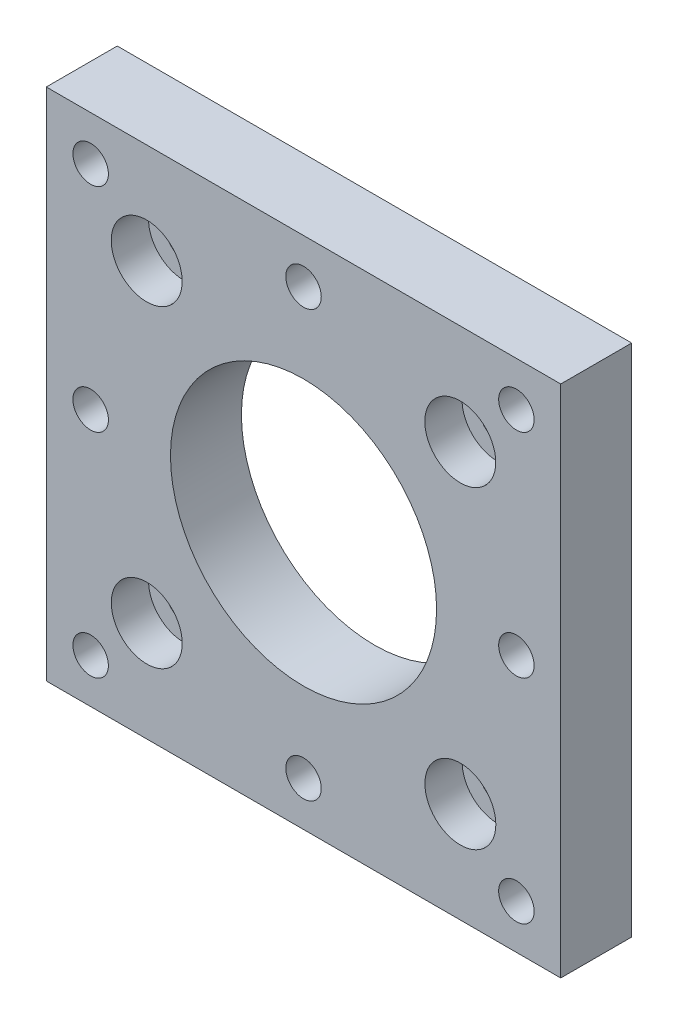
SolidWorks part; units mm, degrees
ref_plane "Front Plane" through (0, 0, 0) normal (0, 0, 1) x (1, 0, 0)
ref_plane "Top Plane" through (0, 0, 0) normal (0, 1, 0) x (1, 0, 0)
ref_plane "Right Plane" through (0, 0, 0) normal (1, 0, 0) x (0, 0, -1)
sketch "Sketch1" plane through (0, 0, 0) normal (0, 0, 1) x (1, 0, 0)
  line L0 (0, 0) -> (0, 24) construction
  line L1 (-29, -29) -> (29, -29)
  line L2 (-29, -29) -> (-29, 29)
  line L3 (-29, 29) -> (29, 29)
  line L4 (29, -29) -> (29, 29)
  line L5 (-29, -29) -> (29, 29) construction
  line L6 (-29, 29) -> (29, -29) construction
  line L7 (-29, 0) -> (29, 0) construction
  circle A0 centre (0, 0) radius 15
  circle A1 centre (0, 24) radius 2
  circle A7 centre (-24, 24) radius 2
  circle A8 centre (24, 0) radius 2
  circle A9 centre (0, -24) radius 2
  circle A10 centre (-24, 0) radius 2
  circle A11 centre (24, -24) radius 2
  circle A12 centre (24, 24) radius 2
  circle A13 centre (-24, -24) radius 2
  point P0 (0, 0)
  point P21 (0, 0)
  point P22 (-3.4641, 2)
  dimension "D2" = 30
  dimension "D4" = 4
  dimension "D5" = 4
  dimension "D6" = 4
  dimension "D1" = 58
  dimension "D3" = 24
extrude "Boss-Extrude1" add sketch "Sketch1" along normal blind 8
sketch "Sketch3" plane through (0, 0, 0) normal (0, 0, -1) x (-1, 0, 0)
  line L0 (29, -29) -> (-29, 29) construction
  line L1 (-29, 29) -> (29, 29) construction
  line L2 (-29, -29) -> (29, 29) construction
  circle A1 centre (-17.6734, 17.6819) radius 2
  circle A2 centre (17.6819, 17.6734) radius 2
  circle A3 centre (17.6734, -17.6819) radius 2
  circle A4 centre (-17.6819, -17.6734) radius 2
  point P23 (0, 0)
  dimension "D2" = 4
  dimension "D3" = 4
extrude "Cut-Extrude1" cut sketch "Sketch3" against normal through all
sketch "Sketch4" plane through (0, 0, 8) normal (0, 0, 1) x (1, 0, 0)
  circle A0 centre (-17.6819, 17.6734) radius 4
  circle A1 centre (17.6734, 17.6819) radius 4
  circle A2 centre (17.6819, -17.6734) radius 4
  circle A3 centre (-17.6734, -17.6819) radius 4
  point P12 (0, 0)
  dimension "D1" = 8
  dimension "D2" = 4
extrude "Cut-Extrude2" cut sketch "Sketch4" against normal blind 4.2
